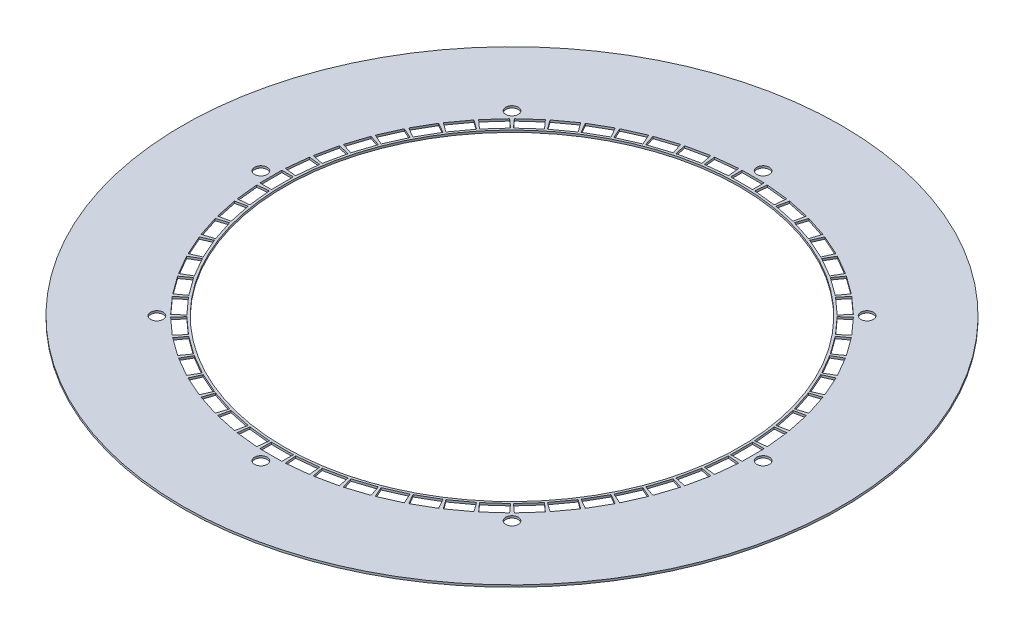
SolidWorks part; units mm, degrees
material "2024-T4"
ref_plane "Front Plane" through (0, 0, 0) normal (0, 0, 1) x (1, 0, 0)
ref_plane "Top Plane" through (0, 0, 0) normal (0, 1, 0) x (1, 0, 0)
ref_plane "Right Plane" through (0, 0, 0) normal (1, 0, 0) x (0, 0, -1)
sketch "Sketch1" plane through (0, 0, 0) normal (0, 1, 0) x (1, 0, 0)
  line L0 (0, -1000) -> (0, 49000) construction
  line L1 (-1000, 0) -> (49000, 0) construction
  line L2 (13.6513, 230.3348) -> (12.5015, 219.3951)
  line L3 (-10.5, 230.5) -> (10.5, 230.5)
  line L4 (-10.5, 230.5) -> (-10.5, 219.5)
  line L5 (-10.5, 219.5) -> (10.5, 219.5)
  line L6 (10.5, 230.5) -> (10.5, 219.5)
  line L7 (-10.5, 230.5) -> (10.5, 219.5) construction
  line L8 (-10.5, 219.5) -> (10.5, 230.5) construction
  line L9 (13.6513, 230.3348) -> (34.5363, 228.1397)
  line L10 (34.5363, 228.1397) -> (33.3865, 217.2)
  line L11 (12.5015, 219.3951) -> (33.3865, 217.2)
  line L12 (37.6531, 227.6461) -> (35.3661, 216.8865)
  line L13 (37.6531, 227.6461) -> (58.1942, 223.2799)
  line L14 (58.1942, 223.2799) -> (55.9072, 212.5203)
  line L15 (35.3661, 216.8865) -> (55.9072, 212.5203)
  line L16 (61.2423, 222.4632) -> (57.8431, 212.0016)
  line L17 (61.2423, 222.4632) -> (81.2145, 215.9738)
  line L18 (81.2145, 215.9738) -> (77.8153, 205.5122)
  line L19 (57.8431, 212.0016) -> (77.8153, 205.5122)
  line L20 (84.1606, 214.843) -> (79.6865, 204.794)
  line L21 (84.1606, 214.843) -> (103.345, 206.3015)
  line L22 (103.345, 206.3015) -> (98.8709, 196.2525)
  line L23 (79.6865, 204.794) -> (98.8709, 196.2525)
  line L24 (106.1567, 204.8689) -> (100.6567, 195.3426)
  line L25 (106.1567, 204.8689) -> (124.3433, 194.3689)
  line L26 (124.3433, 194.3689) -> (118.8433, 184.8426)
  line L27 (100.6567, 195.3426) -> (118.8433, 184.8426)
  line L28 (126.9898, 192.6502) -> (120.5242, 183.751)
  line L29 (126.9898, 192.6502) -> (143.9792, 180.3067)
  line L30 (143.9792, 180.3067) -> (137.5135, 171.4075)
  line L31 (120.5242, 183.751) -> (137.5135, 171.4075)
  line L32 (146.4316, 178.3208) -> (139.0711, 170.1462)
  line L33 (146.4316, 178.3208) -> (162.0376, 164.269)
  line L34 (162.0376, 164.269) -> (154.6772, 156.0944)
  line L35 (139.0711, 170.1462) -> (154.6772, 156.0944)
  line L36 (164.269, 162.0376) -> (156.0944, 154.6772)
  line L37 (164.269, 162.0376) -> (178.3208, 146.4316)
  line L38 (178.3208, 146.4316) -> (170.1462, 139.0711)
  line L39 (156.0944, 154.6772) -> (170.1462, 139.0711)
  line L40 (180.3067, 143.9792) -> (171.4075, 137.5135)
  line L41 (180.3067, 143.9792) -> (192.6502, 126.9898)
  line L42 (192.6502, 126.9898) -> (183.751, 120.5242)
  line L43 (171.4075, 137.5135) -> (183.751, 120.5242)
  line L44 (194.3689, 124.3433) -> (184.8426, 118.8433)
  line L45 (194.3689, 124.3433) -> (204.8689, 106.1567)
  line L46 (204.8689, 106.1567) -> (195.3426, 100.6567)
  line L47 (184.8426, 118.8433) -> (195.3426, 100.6567)
  line L48 (206.3015, 103.345) -> (196.2525, 98.8709)
  line L49 (206.3015, 103.345) -> (214.843, 84.1606)
  line L50 (214.843, 84.1606) -> (204.794, 79.6865)
  line L51 (196.2525, 98.8709) -> (204.794, 79.6865)
  line L52 (215.9738, 81.2145) -> (205.5122, 77.8153)
  line L53 (215.9738, 81.2145) -> (222.4632, 61.2423)
  line L54 (222.4632, 61.2423) -> (212.0016, 57.8431)
  line L55 (205.5122, 77.8153) -> (212.0016, 57.8431)
  line L56 (223.2799, 58.1942) -> (212.5203, 55.9072)
  line L57 (223.2799, 58.1942) -> (227.6461, 37.6531)
  line L58 (227.6461, 37.6531) -> (216.8865, 35.3661)
  line L59 (212.5203, 55.9072) -> (216.8865, 35.3661)
  line L60 (228.1397, 34.5363) -> (217.2, 33.3865)
  line L61 (228.1397, 34.5363) -> (230.3348, 13.6513)
  line L62 (230.3348, 13.6513) -> (219.3951, 12.5015)
  line L63 (217.2, 33.3865) -> (219.3951, 12.5015)
  line L64 (230.5, 10.5) -> (219.5, 10.5)
  line L65 (230.5, 10.5) -> (230.5, -10.5)
  line L66 (230.5, -10.5) -> (219.5, -10.5)
  line L67 (219.5, 10.5) -> (219.5, -10.5)
  line L68 (230.3348, -13.6513) -> (219.3951, -12.5015)
  line L69 (230.3348, -13.6513) -> (228.1397, -34.5363)
  line L70 (228.1397, -34.5363) -> (217.2, -33.3865)
  line L71 (219.3951, -12.5015) -> (217.2, -33.3865)
  line L72 (227.6461, -37.6531) -> (216.8865, -35.3661)
  line L73 (227.6461, -37.6531) -> (223.2799, -58.1942)
  line L74 (223.2799, -58.1942) -> (212.5203, -55.9072)
  line L75 (216.8865, -35.3661) -> (212.5203, -55.9072)
  line L76 (222.4632, -61.2423) -> (212.0016, -57.8431)
  line L77 (222.4632, -61.2423) -> (215.9738, -81.2145)
  line L78 (215.9738, -81.2145) -> (205.5122, -77.8153)
  line L79 (212.0016, -57.8431) -> (205.5122, -77.8153)
  line L80 (214.843, -84.1606) -> (204.794, -79.6865)
  line L81 (214.843, -84.1606) -> (206.3015, -103.345)
  line L82 (206.3015, -103.345) -> (196.2525, -98.8709)
  line L83 (204.794, -79.6865) -> (196.2525, -98.8709)
  line L84 (204.8689, -106.1567) -> (195.3426, -100.6567)
  line L85 (204.8689, -106.1567) -> (194.3689, -124.3433)
  line L86 (194.3689, -124.3433) -> (184.8426, -118.8433)
  line L87 (195.3426, -100.6567) -> (184.8426, -118.8433)
  line L88 (192.6502, -126.9898) -> (183.751, -120.5242)
  line L89 (192.6502, -126.9898) -> (180.3067, -143.9792)
  line L90 (180.3067, -143.9792) -> (171.4075, -137.5135)
  line L91 (183.751, -120.5242) -> (171.4075, -137.5135)
  line L92 (178.3208, -146.4316) -> (170.1462, -139.0711)
  line L93 (178.3208, -146.4316) -> (164.269, -162.0376)
  line L94 (164.269, -162.0376) -> (156.0944, -154.6772)
  line L95 (170.1462, -139.0711) -> (156.0944, -154.6772)
  line L96 (162.0376, -164.269) -> (154.6772, -156.0944)
  line L97 (162.0376, -164.269) -> (146.4316, -178.3208)
  line L98 (146.4316, -178.3208) -> (139.0711, -170.1462)
  line L99 (154.6772, -156.0944) -> (139.0711, -170.1462)
  line L100 (143.9792, -180.3067) -> (137.5135, -171.4075)
  line L101 (143.9792, -180.3067) -> (126.9898, -192.6502)
  line L102 (126.9898, -192.6502) -> (120.5242, -183.751)
  line L103 (137.5135, -171.4075) -> (120.5242, -183.751)
  line L104 (124.3433, -194.3689) -> (118.8433, -184.8426)
  line L105 (124.3433, -194.3689) -> (106.1567, -204.8689)
  line L106 (106.1567, -204.8689) -> (100.6567, -195.3426)
  line L107 (118.8433, -184.8426) -> (100.6567, -195.3426)
  line L108 (103.345, -206.3015) -> (98.8709, -196.2525)
  line L109 (103.345, -206.3015) -> (84.1606, -214.843)
  line L110 (84.1606, -214.843) -> (79.6865, -204.794)
  line L111 (98.8709, -196.2525) -> (79.6865, -204.794)
  line L112 (81.2145, -215.9738) -> (77.8153, -205.5122)
  line L113 (81.2145, -215.9738) -> (61.2423, -222.4632)
  line L114 (61.2423, -222.4632) -> (57.8431, -212.0016)
  line L115 (77.8153, -205.5122) -> (57.8431, -212.0016)
  line L116 (58.1942, -223.2799) -> (55.9072, -212.5203)
  line L117 (58.1942, -223.2799) -> (37.6531, -227.6461)
  line L118 (37.6531, -227.6461) -> (35.3661, -216.8865)
  line L119 (55.9072, -212.5203) -> (35.3661, -216.8865)
  line L120 (34.5363, -228.1397) -> (33.3865, -217.2)
  line L121 (34.5363, -228.1397) -> (13.6513, -230.3348)
  line L122 (13.6513, -230.3348) -> (12.5015, -219.3951)
  line L123 (33.3865, -217.2) -> (12.5015, -219.3951)
  line L124 (10.5, -230.5) -> (10.5, -219.5)
  line L125 (10.5, -230.5) -> (-10.5, -230.5)
  line L126 (-10.5, -230.5) -> (-10.5, -219.5)
  line L127 (10.5, -219.5) -> (-10.5, -219.5)
  line L128 (-13.6513, -230.3348) -> (-12.5015, -219.3951)
  line L129 (-13.6513, -230.3348) -> (-34.5363, -228.1397)
  line L130 (-34.5363, -228.1397) -> (-33.3865, -217.2)
  line L131 (-12.5015, -219.3951) -> (-33.3865, -217.2)
  line L132 (-37.6531, -227.6461) -> (-35.3661, -216.8865)
  line L133 (-37.6531, -227.6461) -> (-58.1942, -223.2799)
  line L134 (-58.1942, -223.2799) -> (-55.9072, -212.5203)
  line L135 (-35.3661, -216.8865) -> (-55.9072, -212.5203)
  line L136 (-61.2423, -222.4632) -> (-57.8431, -212.0016)
  line L137 (-61.2423, -222.4632) -> (-81.2145, -215.9738)
  line L138 (-81.2145, -215.9738) -> (-77.8153, -205.5122)
  line L139 (-57.8431, -212.0016) -> (-77.8153, -205.5122)
  line L140 (-84.1606, -214.843) -> (-79.6865, -204.794)
  line L141 (-84.1606, -214.843) -> (-103.345, -206.3015)
  line L142 (-103.345, -206.3015) -> (-98.8709, -196.2525)
  line L143 (-79.6865, -204.794) -> (-98.8709, -196.2525)
  line L144 (-106.1567, -204.8689) -> (-100.6567, -195.3426)
  line L145 (-106.1567, -204.8689) -> (-124.3433, -194.3689)
  line L146 (-124.3433, -194.3689) -> (-118.8433, -184.8426)
  line L147 (-100.6567, -195.3426) -> (-118.8433, -184.8426)
  line L148 (-126.9898, -192.6502) -> (-120.5242, -183.751)
  line L149 (-126.9898, -192.6502) -> (-143.9792, -180.3067)
  line L150 (-143.9792, -180.3067) -> (-137.5135, -171.4075)
  line L151 (-120.5242, -183.751) -> (-137.5135, -171.4075)
  line L152 (-146.4316, -178.3208) -> (-139.0711, -170.1462)
  line L153 (-146.4316, -178.3208) -> (-162.0376, -164.269)
  line L154 (-162.0376, -164.269) -> (-154.6772, -156.0944)
  line L155 (-139.0711, -170.1462) -> (-154.6772, -156.0944)
  line L156 (-164.269, -162.0376) -> (-156.0944, -154.6772)
  line L157 (-164.269, -162.0376) -> (-178.3208, -146.4316)
  line L158 (-178.3208, -146.4316) -> (-170.1462, -139.0711)
  line L159 (-156.0944, -154.6772) -> (-170.1462, -139.0711)
  line L160 (-180.3067, -143.9792) -> (-171.4075, -137.5135)
  line L161 (-180.3067, -143.9792) -> (-192.6502, -126.9898)
  line L162 (-192.6502, -126.9898) -> (-183.751, -120.5242)
  line L163 (-171.4075, -137.5135) -> (-183.751, -120.5242)
  line L164 (-194.3689, -124.3433) -> (-184.8426, -118.8433)
  line L165 (-194.3689, -124.3433) -> (-204.8689, -106.1567)
  line L166 (-204.8689, -106.1567) -> (-195.3426, -100.6567)
  line L167 (-184.8426, -118.8433) -> (-195.3426, -100.6567)
  line L168 (-206.3015, -103.345) -> (-196.2525, -98.8709)
  line L169 (-206.3015, -103.345) -> (-214.843, -84.1606)
  line L170 (-214.843, -84.1606) -> (-204.794, -79.6865)
  line L171 (-196.2525, -98.8709) -> (-204.794, -79.6865)
  line L172 (-215.9738, -81.2145) -> (-205.5122, -77.8153)
  line L173 (-215.9738, -81.2145) -> (-222.4632, -61.2423)
  line L174 (-222.4632, -61.2423) -> (-212.0016, -57.8431)
  line L175 (-205.5122, -77.8153) -> (-212.0016, -57.8431)
  line L176 (-223.2799, -58.1942) -> (-212.5203, -55.9072)
  line L177 (-223.2799, -58.1942) -> (-227.6461, -37.6531)
  line L178 (-227.6461, -37.6531) -> (-216.8865, -35.3661)
  line L179 (-212.5203, -55.9072) -> (-216.8865, -35.3661)
  line L180 (-228.1397, -34.5363) -> (-217.2, -33.3865)
  line L181 (-228.1397, -34.5363) -> (-230.3348, -13.6513)
  line L182 (-230.3348, -13.6513) -> (-219.3951, -12.5015)
  line L183 (-217.2, -33.3865) -> (-219.3951, -12.5015)
  line L184 (-230.5, -10.5) -> (-219.5, -10.5)
  line L185 (-230.5, -10.5) -> (-230.5, 10.5)
  line L186 (-230.5, 10.5) -> (-219.5, 10.5)
  line L187 (-219.5, -10.5) -> (-219.5, 10.5)
  line L188 (-230.3348, 13.6513) -> (-219.3951, 12.5015)
  line L189 (-230.3348, 13.6513) -> (-228.1397, 34.5363)
  line L190 (-228.1397, 34.5363) -> (-217.2, 33.3865)
  line L191 (-219.3951, 12.5015) -> (-217.2, 33.3865)
  line L192 (-227.6461, 37.6531) -> (-216.8865, 35.3661)
  line L193 (-227.6461, 37.6531) -> (-223.2799, 58.1942)
  line L194 (-223.2799, 58.1942) -> (-212.5203, 55.9072)
  line L195 (-216.8865, 35.3661) -> (-212.5203, 55.9072)
  line L196 (-222.4632, 61.2423) -> (-212.0016, 57.8431)
  line L197 (-222.4632, 61.2423) -> (-215.9738, 81.2145)
  line L198 (-215.9738, 81.2145) -> (-205.5122, 77.8153)
  line L199 (-212.0016, 57.8431) -> (-205.5122, 77.8153)
  line L200 (-214.843, 84.1606) -> (-204.794, 79.6865)
  line L201 (-214.843, 84.1606) -> (-206.3015, 103.345)
  line L202 (-206.3015, 103.345) -> (-196.2525, 98.8709)
  line L203 (-204.794, 79.6865) -> (-196.2525, 98.8709)
  line L204 (-204.8689, 106.1567) -> (-195.3426, 100.6567)
  line L205 (-204.8689, 106.1567) -> (-194.3689, 124.3433)
  line L206 (-194.3689, 124.3433) -> (-184.8426, 118.8433)
  line L207 (-195.3426, 100.6567) -> (-184.8426, 118.8433)
  line L208 (-192.6502, 126.9898) -> (-183.751, 120.5242)
  line L209 (-192.6502, 126.9898) -> (-180.3067, 143.9792)
  line L210 (-180.3067, 143.9792) -> (-171.4075, 137.5135)
  line L211 (-183.751, 120.5242) -> (-171.4075, 137.5135)
  line L212 (-178.3208, 146.4316) -> (-170.1462, 139.0711)
  line L213 (-178.3208, 146.4316) -> (-164.269, 162.0376)
  line L214 (-164.269, 162.0376) -> (-156.0944, 154.6772)
  line L215 (-170.1462, 139.0711) -> (-156.0944, 154.6772)
  line L216 (-162.0376, 164.269) -> (-154.6772, 156.0944)
  line L217 (-162.0376, 164.269) -> (-146.4316, 178.3208)
  line L218 (-146.4316, 178.3208) -> (-139.0711, 170.1462)
  line L219 (-154.6772, 156.0944) -> (-139.0711, 170.1462)
  line L220 (-143.9792, 180.3067) -> (-137.5135, 171.4075)
  line L221 (-143.9792, 180.3067) -> (-126.9898, 192.6502)
  line L222 (-126.9898, 192.6502) -> (-120.5242, 183.751)
  line L223 (-137.5135, 171.4075) -> (-120.5242, 183.751)
  line L224 (-124.3433, 194.3689) -> (-118.8433, 184.8426)
  line L225 (-124.3433, 194.3689) -> (-106.1567, 204.8689)
  line L226 (-106.1567, 204.8689) -> (-100.6567, 195.3426)
  line L227 (-118.8433, 184.8426) -> (-100.6567, 195.3426)
  line L228 (-103.345, 206.3015) -> (-98.8709, 196.2525)
  line L229 (-103.345, 206.3015) -> (-84.1606, 214.843)
  line L230 (-84.1606, 214.843) -> (-79.6865, 204.794)
  line L231 (-98.8709, 196.2525) -> (-79.6865, 204.794)
  line L232 (-81.2145, 215.9738) -> (-77.8153, 205.5122)
  line L233 (-81.2145, 215.9738) -> (-61.2423, 222.4632)
  line L234 (-61.2423, 222.4632) -> (-57.8431, 212.0016)
  line L235 (-77.8153, 205.5122) -> (-57.8431, 212.0016)
  line L236 (-58.1942, 223.2799) -> (-55.9072, 212.5203)
  line L237 (-58.1942, 223.2799) -> (-37.6531, 227.6461)
  line L238 (-37.6531, 227.6461) -> (-35.3661, 216.8865)
  line L239 (-55.9072, 212.5203) -> (-35.3661, 216.8865)
  line L240 (-34.5363, 228.1397) -> (-33.3865, 217.2)
  line L241 (-34.5363, 228.1397) -> (-13.6513, 230.3348)
  line L242 (-13.6513, 230.3348) -> (-12.5015, 219.3951)
  line L243 (-33.3865, 217.2) -> (-12.5015, 219.3951)
  circle A0 centre (0, 0) radius 315
  circle A1 centre (0, 0) radius 217.5
  circle A2 centre (0, 240) radius 6
  circle A3 centre (169.7056, 169.7056) radius 6
  circle A4 centre (240, 0) radius 6
  circle A5 centre (169.7056, -169.7056) radius 6
  circle A6 centre (0, -240) radius 6
  circle A7 centre (-169.7056, -169.7056) radius 6
  circle A8 centre (-240, 0) radius 6
  circle A9 centre (-169.7056, 169.7056) radius 6
  point P4 (0, 225)
  point P252 (0, 0)
  point P268 (0, 0)
  dimension "D1" = 630
  dimension "D2" = 435
  dimension "D7" = 12
  dimension "D3" = 21
  dimension "D4" = 11
  dimension "D5" = 225
  dimension "D8" = 240
  dimension "D6" = 60
  dimension "D9" = 8
extrude "Boss-Extrude1" add sketch "Sketch1" along normal mid plane 2
